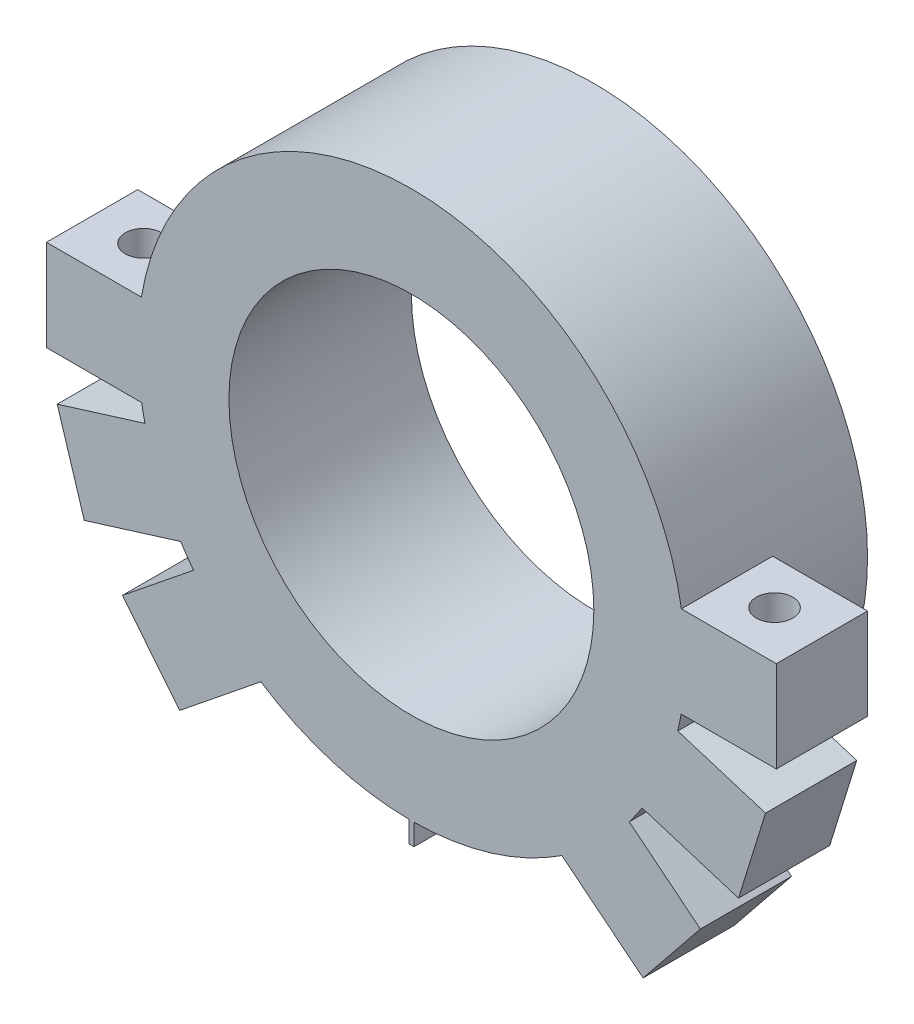
SolidWorks part; units mm, degrees
ref_plane "Plan de face" through (0, 0, 0) normal (0, 0, 1) x (1, 0, 0)
ref_plane "Plan de dessus" through (0, 0, 0) normal (0, 1, 0) x (1, 0, 0)
ref_plane "Plan de droite" through (0, 0, 0) normal (1, 0, 0) x (0, 0, -1)
sketch "Esquisse1" plane through (0, 0, 0) normal (0, 0, 1) x (1, 0, 0)
  circle A0 centre (0, 0) radius 10
  circle A1 centre (0, 0) radius 15
  dimension "D1" = 20
  dimension "D2" = 30
extrude "Boss.-Extru.1" add sketch "Esquisse1" along normal blind 10
sketch "Esquisse2" plane through (0, 0, 10) normal (0, 0, 1) x (1, 0, 0)
  line L12 (27.2852, 0) -> (-27.2852, 0) construction
  line L26 (0, 20.4609) -> (0, -20.4609) construction
  line L39 (-13, 2.4544) -> (-13, -2.5456)
  line L40 (-13, 2.4544) -> (-20, 2.4544)
  line L41 (-13, -2.5456) -> (-20, -2.5456)
  line L42 (-20, 2.4544) -> (-20, -2.5456)
  line L43 (-12.7237, -2.8603) -> (-11.2428, -7.6359)
  line L44 (-12.7237, -2.8603) -> (-19.4096, -4.9336)
  line L45 (-11.2428, -7.6359) -> (-17.9287, -9.7092)
  line L46 (-19.4096, -4.9336) -> (-17.9287, -9.7092)
  line L47 (-10.3863, -7.8296) -> (-7.2488, -11.7227)
  line L48 (-10.3863, -7.8296) -> (-15.8366, -12.2221)
  line L49 (-7.2488, -11.7227) -> (-12.6991, -16.1152)
  line L50 (-15.8366, -12.2221) -> (-12.6991, -16.1152)
  line L51 (15.8366, -12.2221) -> (12.6991, -16.1152)
  line L52 (7.2488, -11.7227) -> (12.6991, -16.1152)
  line L53 (10.3863, -7.8296) -> (15.8366, -12.2221)
  line L54 (10.3863, -7.8296) -> (7.2488, -11.7227)
  line L55 (19.4096, -4.9336) -> (17.9287, -9.7092)
  line L56 (11.2428, -7.6359) -> (17.9287, -9.7092)
  line L57 (12.7237, -2.8603) -> (19.4096, -4.9336)
  line L58 (12.7237, -2.8603) -> (11.2428, -7.6359)
  line L59 (20, 2.4544) -> (20, -2.5456)
  line L60 (13, -2.5456) -> (20, -2.5456)
  line L61 (13, 2.4544) -> (20, 2.4544)
  line L62 (13, 2.4544) -> (13, -2.5456)
  line L63 (-0.1424, -14.6382) -> (-0.1424, -16.1644)
  line L64 (0.1424, -14.6382) -> (-0.1424, -14.6382)
  line L65 (0.1424, -14.6382) -> (0.1424, -16.1644)
  line L66 (0.1424, -16.1644) -> (-0.1424, -16.1644)
  point P30 (-11.2428, -7.6359)
  point P32 (-11.2481, -7.3012)
  point P35 (-16.4224, -11.4952)
  dimension "D1" = 5
  dimension "D2" = 7
  dimension "D3" = 13
  dimension "D4" = 5
  dimension "D5" = 7
  dimension "D6" = 13
  dimension "D7" = 5
  dimension "D8" = 7
  dimension "D9" = 13
extrude "Boss.-Extru.2" add sketch "Esquisse2" against normal blind 5
sketch "Esquisse3" plane through (0, -2.5456, 0) normal (0, -1, 0) x (1, 0, 0)
  circle A0 centre (-17.2923, 7.3893) radius 1
  dimension "D1" = 2
extrude "Enlèv. mat.-Extru.1" cut sketch "Esquisse3" against normal blind 10
sketch "Esquisse4" plane through (1.1739, -3.7854, 0) normal (0.2962, -0.9551, 0) x (0.9551, 0.2962, 0)
  circle A0 centre (-17.5659, 7.2675) radius 1
  dimension "D1" = 2
extrude "Enlèv. mat.-Extru.2" cut sketch "Esquisse4" against normal blind 7
sketch "Esquisse5" plane through (2.8733, -3.5652, 0) normal (0.6275, -0.7786, 0) x (0.7786, 0.6275, 0)
  circle A0 centre (-16.8984, 6.9351) radius 1
  dimension "D1" = 2
extrude "Enlèv. mat.-Extru.3" cut sketch "Esquisse5" against normal blind 7
mirror "Symétrie1" about plane through (0, 0, 0) normal (1, 0, 0) of "Enlèv. mat.-Extru.2", "Enlèv. mat.-Extru.1", "Enlèv. mat.-Extru.3"
